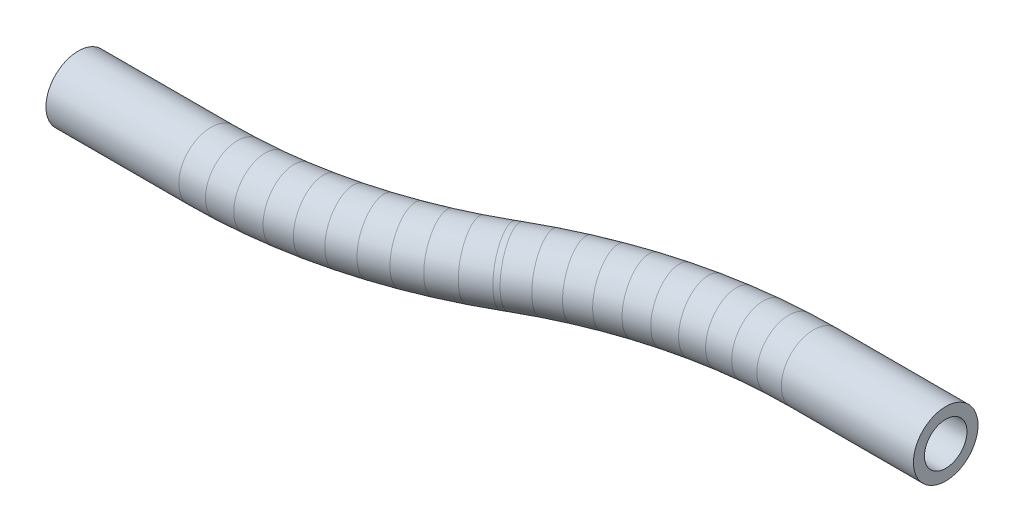
SolidWorks part; units mm, degrees
ref_plane "Front Plane" through (0, 0, 0) normal (0, 0, 1) x (1, 0, 0)
ref_plane "Top Plane" through (0, 0, 0) normal (0, 1, 0) x (1, 0, 0)
ref_plane "Right Plane" through (0, 0, 0) normal (1, 0, 0) x (0, 0, -1)
sketch3d "Path"
  line L0 (-140, 103.057, 59.5) -> (-115.3874, 103.057, 59.5)
  line L1 (-115.3874, 103.057, 59.5) -> (-110.7354, 103.0679, 59.3944)
  line L2 (-110.7354, 103.0679, 59.3944) -> (-106.0931, 103.1006, 59.0779)
  line L3 (-106.0931, 103.1006, 59.0779) -> (-101.4701, 103.155, 58.5511)
  line L4 (-101.4701, 103.155, 58.5511) -> (-96.876, 103.231, 57.8151)
  line L5 (-96.876, 103.231, 57.8151) -> (-92.3205, 103.3285, 56.8715)
  line L6 (-92.3205, 103.3285, 56.8715) -> (-87.8131, 103.4471, 55.7222)
  line L7 (-87.8131, 103.4471, 55.7222) -> (-83.363, 103.5868, 54.3696)
  line L8 (-83.363, 103.5868, 54.3696) -> (-78.9795, 103.7472, 52.8165)
  line L9 (-78.9795, 103.7472, 52.8165) -> (-74.6718, 103.9279, 51.0662)
  line L10 (-74.6718, 103.9279, 51.0662) -> (-70.4489, 104.1287, 49.1222)
  line L11 (-70.4489, 104.1287, 49.1222) -> (-69.5511, 104.1739, 48.684)
  line L12 (-69.5511, 104.1739, 48.684) -> (-65.3282, 104.3747, 46.7401)
  line L13 (-65.3282, 104.3747, 46.7401) -> (-61.0205, 104.5554, 44.9897)
  line L14 (-61.0205, 104.5554, 44.9897) -> (-56.637, 104.7158, 43.4367)
  line L15 (-56.637, 104.7158, 43.4367) -> (-52.1869, 104.8555, 42.0841)
  line L16 (-52.1869, 104.8555, 42.0841) -> (-47.6795, 104.9741, 40.9347)
  line L17 (-47.6795, 104.9741, 40.9347) -> (-43.124, 105.0716, 39.9911)
  line L18 (-43.124, 105.0716, 39.9911) -> (-38.5299, 105.1476, 39.2551)
  line L19 (-38.5299, 105.1476, 39.2551) -> (-33.9069, 105.202, 38.7283)
  line L20 (-33.9069, 105.202, 38.7283) -> (-29.2646, 105.2347, 38.4118)
  line L21 (-29.2646, 105.2347, 38.4118) -> (-24.6126, 105.2456, 38.3063)
  line L22 (-24.6126, 105.2456, 38.3063) -> (0, 105.2456, 38.3063)
ref_plane "Start Plane" through (-140, 0, 0) normal (1, 0, 0) x (0, 0, -1)
sketch "Profile" plane through (-140, 0, 0) normal (1, 0, 0) x (0, 0, -1)
  circle A0 centre (-59.5, 103.057) radius 6
  circle A1 centre (-59.5, 103.057) radius 3.95
sweep "Tube" add profiles "Profile" path "Path"
